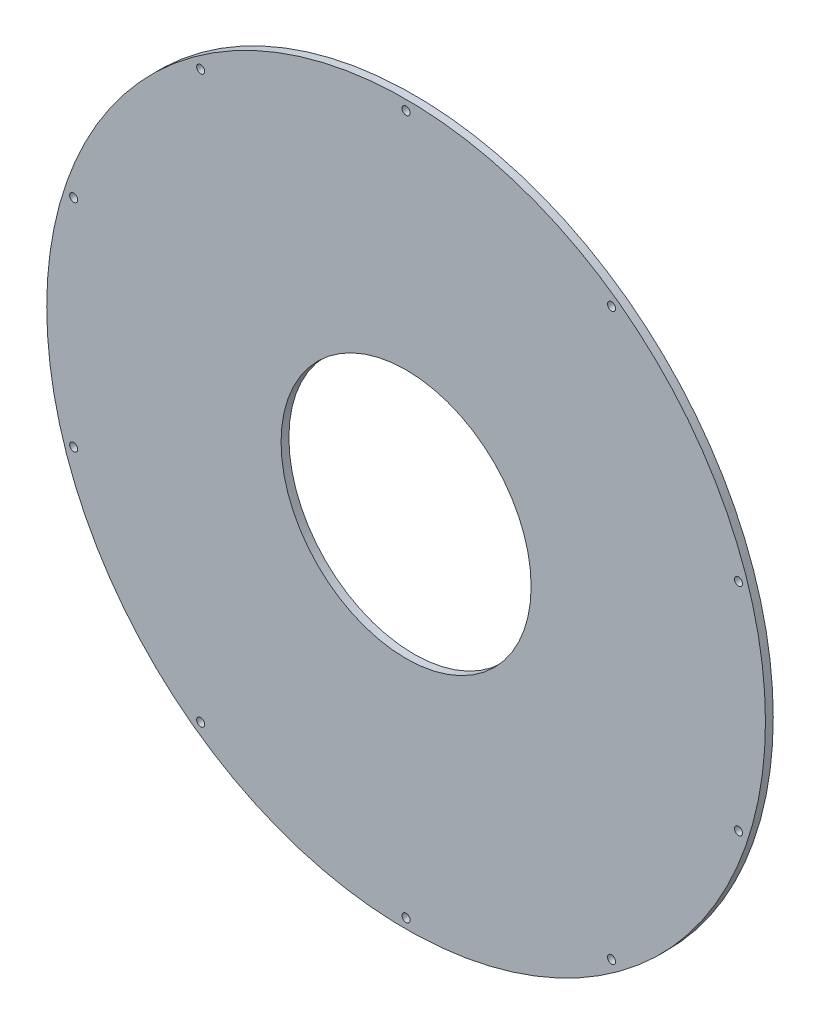
SolidWorks part; units mm, degrees
material "PET"
ref_plane "Front Plane" through (0, 0, 0) normal (0, 0, 1) x (1, 0, 0)
ref_plane "Top Plane" through (0, 0, 0) normal (0, 1, 0) x (1, 0, 0)
ref_plane "Right Plane" through (0, 0, 0) normal (1, 0, 0) x (0, 0, -1)
sketch "Sketch1" plane through (0, 0, 0) normal (0, 0, 1) x (1, 0, 0)
  circle A0 centre (0, 0) radius 146
  circle A1 centre (0, 0) radius 50.8
  dimension "D1" = 292
  dimension "D2" = 101.6
extrude "Boss-Extrude1" add sketch "Sketch1" along normal blind 3.175
hole_wizard "#4 Clearance Hole1" positions "Sketch3" profile "Sketch2" hole size "#4" standard "Ansi Inch" end condition through all
sketch "Sketch3" plane through (0, 0, 3.175) normal (0, 0, 1) x (1, 0, 0)
  point P0 (0, 142)
  dimension "D1" = 142
sketch "Sketch2" plane through (0, 142, 3.175) normal (1, 0, 0) x (0, -1, 0)
  line L0 (0, 0) -> (0, 3.175)
  line L1 (0, 3.175) -> (1.6319, 3.175)
  line L2 (1.6319, 3.175) -> (1.6319, 0)
  line L5 (1.6319, 0) -> (0, 0)
  line L11 (0, -6.35) -> (0, 107.95) construction
  dimension "Thru Hole Dia." = 3.2639
  dimension "Thru Hole Depth" = 3.175
pattern_circular "CirPattern1" count 10 over 360 about axis through (0, 0, 0) along (0, 0, 1) of "#4 Clearance Hole1"
